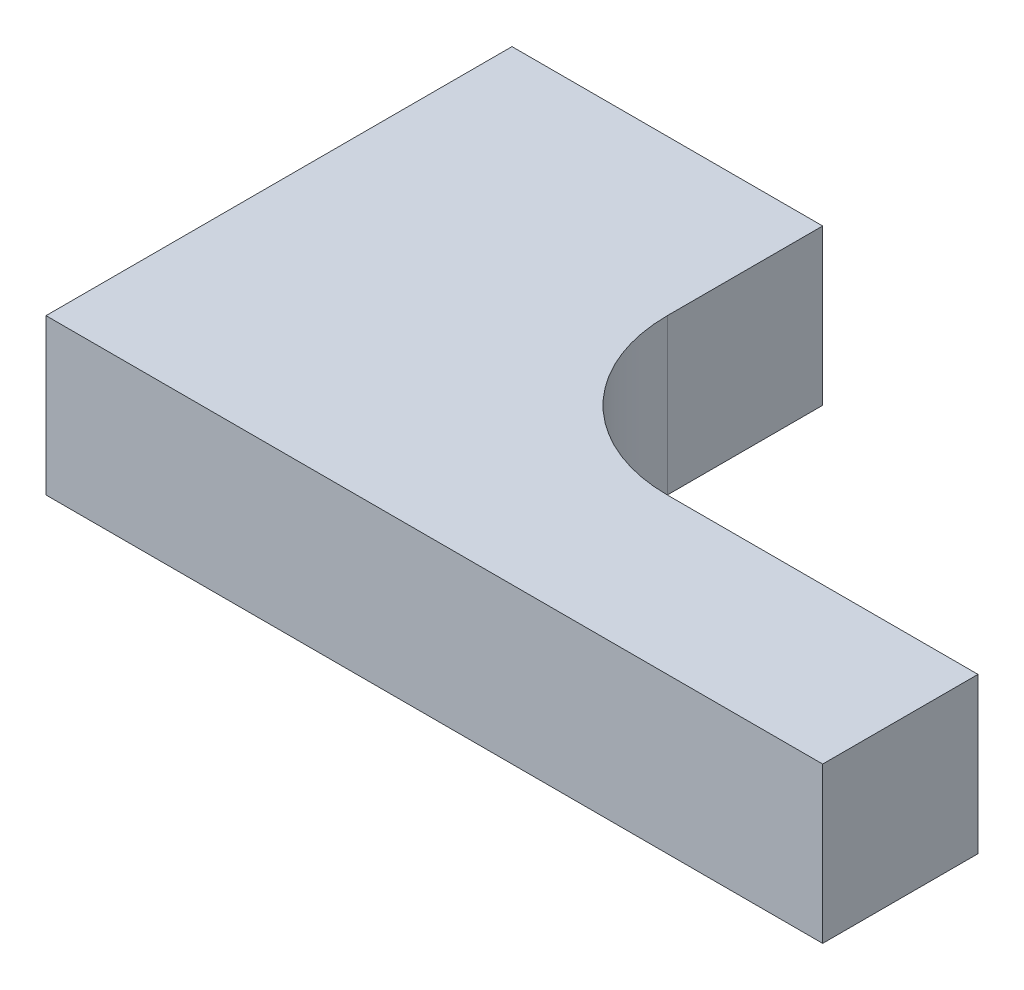
SolidWorks part; units mm, degrees
ref_plane "Přední rovina" through (0, 0, 0) normal (0, 0, 1) x (1, 0, 0)
ref_plane "Horní rovina" through (0, 0, 0) normal (0, 1, 0) x (1, 0, 0)
ref_plane "Pravá rovina" through (0, 0, 0) normal (1, 0, 0) x (0, 0, -1)
sketch "Sketch2" plane through (0, 0, 0) normal (0, 1, 0) x (1, 0, 0)
  line L0 (0, 0) -> (0, -20)
  line L1 (20, -40) -> (60, -40)
  line L2 (60, -40) -> (60, -60)
  line L3 (60, -60) -> (-40, -60)
  line L4 (-40, -60) -> (-40, 0)
  line L5 (-40, 0) -> (0, 0)
  arc A0 (0, -20) -> (20, -40) centre (20, -20) ccw
  dimension "D2" = 20
  dimension "D1" = 40
  dimension "D3" = 40
  dimension "D4" = 20
  dimension "D5" = 20
extrude "Boss-Extrude1" add sketch "Sketch2" along normal blind 20
equation "\"R\"= 20"
equation "\"D2@Sketch2\"=\"R\""
equation "\"D1@Sketch2\"=\"R\" *2"
equation "\"D3@Sketch2\"=\"R\" * 2"
equation "\"D5@Sketch2\"=\"R\""
equation "\"D4@Sketch2\"=\"R\""
